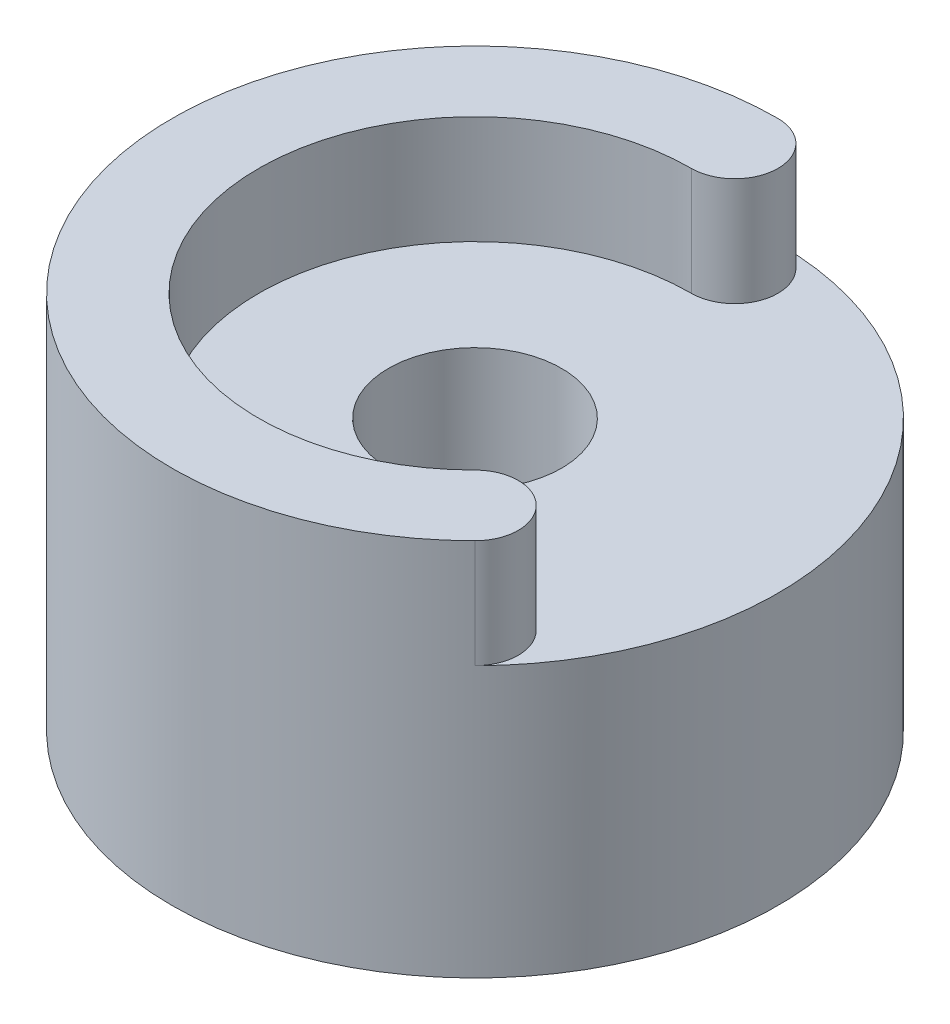
SolidWorks part; units mm, degrees
ref_plane "Front Plane" through (0, 0, 0) normal (0, 0, 1) x (1, 0, 0)
ref_plane "Top Plane" through (0, 0, 0) normal (0, 1, 0) x (1, 0, 0)
ref_plane "Right Plane" through (0, 0, 0) normal (1, 0, 0) x (0, 0, -1)
sketch "Sketch5" plane through (0, 0, 0) normal (0, 1, 0) x (1, 0, 0)
  circle A0 centre (0, 0) radius 4
  circle A1 centre (0, 0) radius 14
extrude "Boss-Extrude3" add sketch "Sketch5" along normal blind 12.5
sketch "Sketch6" plane through (0, 12.5, 0) normal (0, 1, 0) x (1, 0, 0)
  line L0 (0, -44.7868) -> (0, 44.7868) construction
  arc A0 (0, 12) -> (8.4853, -8.4853) centre (0, 0) ccw construction
  arc A1 (0, 14) -> (9.8995, -9.8995) centre (0, 0) ccw
  arc A2 (0, 10) -> (7.0711, -7.0711) centre (0, 0) ccw
  arc A3 (0, 10) -> (0, 14) centre (0, 12) ccw
  arc A4 (9.8995, -9.8995) -> (7.0711, -7.0711) centre (8.4853, -8.4853) ccw
  point P6 (-11.0866, -4.5922)
  dimension "D3" = 12
  dimension "D1" = 4
  dimension "D2" = 225
extrude "Boss-Extrude4" add sketch "Sketch6" along normal blind 5
